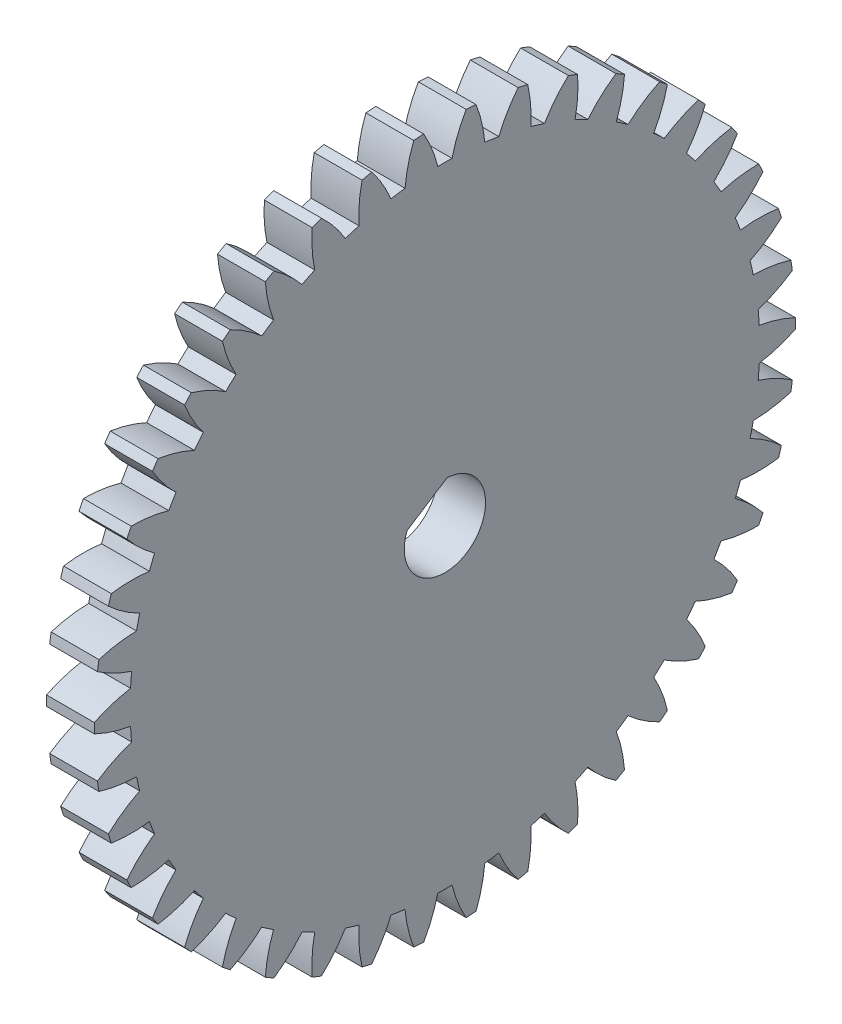
SolidWorks part; units mm, degrees
ref_plane "Plane1" through (0, 0, 0) normal (0, 0, 1) x (1, 0, 0)
ref_plane "Plane2" through (0, 0, 0) normal (0, 1, 0) x (1, 0, 0)
ref_plane "Plane3" through (0, 0, 0) normal (1, 0, 0) x (0, 0, -1)
sketch "HoldingSke" plane through (0, 0, 0) normal (0, 1, 0) x (1, 0, 0)
  line L0 (0, 0) -> (0.7431, -0.6691)
  line L1 (-15, 0) -> (100, 0) construction
  line L2 (0, 0) -> (-2.1039, 2.3779)
  line L3 (0, 0) -> (-11.863, 4.5341)
  line L4 (0, 0) -> (6.4178, 5.7786)
  line L5 (0, 0) -> (-46.8476, -17.4728)
  line L6 (0, 0) -> (-2.4869, -1.6779)
  line L7 (-2.1039, 2.3779) -> (8.6586, 51.2059)
  line L8 (-76.2, 54.61) -> (-76.1, 54.61)
  line L9 (-71.009, 38.7566) -> (-53.1078, 45.2721)
  line L10 (-76.2, 71.12) -> (104.1128, 71.12)
  line L11 (0, 0) -> (-3, 0)
  line L12 (-76.2, 101.6) -> (-76.162, 101.6)
  line L13 (24.9733, 27.94) -> (52.9518, 28.4284)
  line L14 (24.9733, 27.94) -> (24.9743, 27.94)
  line L15 (24.9733, 27.94) -> (100.4006, 29.5858)
  line L16 (-63.627, -1) -> (-12.827, -1)
  circle A0 centre (0, 0) radius 0.5
  circle A1 centre (0, 0) radius 19.749
  circle A2 centre (0, 0) radius 37.5
  circle A3 centre (0, 0) radius 0.5
  dimension "MHD" = 39.498
  dimension "Hub_dia" = 75
  dimension "Bore" = 1
  dimension "MBD" = 1
  dimension "Num_teeth" = 42
  dimension "Pitch" = 1
  dimension "Overall_len" = 50
  dimension "Show_teeth" = 42
  dimension "Thickness" = 3
  dimension "OAL" = 50.0001
  dimension "T_dim" = 0.1
  dimension "Ap" = 20
  dimension "H" = 19.05
  dimension "Pitch_radius" = 180.3128
  dimension "Width" = 3
  dimension "Backlash" = 0.038
  dimension "Addendum_fac" = 1
  dimension "Dedendum_fac" = 1.25
  dimension "Clearance_fac" = 0.25
  dimension "Dedendum_add" = 0.001
  dimension "Module" = 1
sketch "BasProSke" plane through (0, 0, 0) normal (0, 1, 0) x (1, 0, 0)
  line L0 (-10, 0) -> (60, 0) construction
  line L1 (0, 0) -> (0, 22)
  line L2 (0, 0) -> (3, 0)
  line L3 (3, 0) -> (3, 22)
  line L4 (3, 22) -> (0, 22)
  dimension "Thickness" = 3
  dimension "Diameter" = 44
revolve "Base-Revolve" add sketch "BasProSke" angle 360 about L0
sketch "TooCutSke" plane through (0, 0, 0) normal (1, 0, 0) x (0, 0, -1)
  line L1 (0, 0) -> (0, 107) construction
  line L2 (0, 0) -> (-0.8517, 20.9827) construction
  line L3 (0, 0) -> (-3.1368, 41.858) construction
  line L4 (-0.8517, 20.9827) -> (-1.5684, 20.929) construction
  arc A0 (0.4461, 19.744) -> (-0.4461, 19.744) centre (0, 0) ccw
  arc A1 (1.3487, 21.9841) -> (-1.3487, 21.9841) centre (0, 0) ccw
  circle A2 centre (0, 0) radius 21 construction
  circle A3 centre (0, 0) radius 19.7335 construction
  arc A4 (-0.4461, 19.744) -> (-1.3487, 21.9841) centre (-8.6078, 17.7572) ccw
  arc A5 (1.3487, 21.9841) -> (0.4461, 19.744) centre (8.6078, 17.7572) ccw
  dimension "Root_dia" = 39.498
  dimension "Overcut_dia" = 44.0508
  dimension "Pitch_dia" = 42
  dimension "Base_dia" = 39.4671
  dimension "Flank_rad" = 8.4
  dimension "Half_ang" = 4.286
  dimension "Half_CT" = 0.7187
extrude "ToothCut" cut sketch "TooCutSke" along normal through all
fillet "Breaks" [suppressed] radius 0.02
fillet "RootFillets" [suppressed] radius 0.251
pattern_circular "TeethCuts" count 42 every 8.571 about axis through (-10, 0, 0) along (1, 0, 0) of "ToothCut", "RootFillets", "Breaks"
sketch "HubNeaOneSke" plane through (0, 0, 0) normal (-1, 0, 0) x (0, 0, 1)
  circle A0 centre (0, 0) radius 19.749
  dimension "Diameter" = 39.498
extrude "HubNearOne" [suppressed] add sketch "HubNeaOneSke" along normal blind 47.0001
sketch "HubNeaBotSke" plane through (0, 0, 0) normal (-1, 0, 0) x (0, 0, 1)
  circle A0 centre (0, 0) radius 19.749
  dimension "Diameter" = 39.498
extrude "HubNearBoth" [suppressed] add sketch "HubNeaBotSke" along normal blind 23.5
ref_plane "FarPln" through (3, 0, 0) normal (1, 0, 0) x (0, 0, -1)
sketch "HubFarSke" plane through (3, 0, 0) normal (1, 0, 0) x (0, 0, -1)
  circle A0 centre (0, 0) radius 19.749
  dimension "Diameter" = 39.498
extrude "HubFar" [suppressed] add sketch "HubFarSke" along normal blind 23.5
sketch "BorSke" plane through (0, 0, 0) normal (1, 0, 0) x (0, 0, -1)
  line L0 (-2.38, 0.9154) -> (0.138, 2.5463)
  arc A0 (-2.38, 0.9154) -> (0.138, 2.5463) centre (0, 0) ccw
  dimension "D1" = 3
  dimension "D2" = 2.55
extrude "Bore" cut sketch "BorSke" along normal mid plane 100.0001
sketch "KeySke" plane through (0, 0, 0) normal (1, 0, 0) x (0, 0, -1)
  line L0 (-0.05, 0) -> (-0.05, 0.6)
  line L1 (-0.05, 0.6) -> (0.05, 0.6)
  line L2 (0.05, 0.6) -> (0.05, 0)
  line L3 (0, 0) -> (0, 34) construction
  line L4 (-0.05, 0) -> (0.05, 0)
  dimension "Offset" = 0.6
  dimension "Width" = 0.1
extrude "Keyway" [suppressed] cut sketch "KeySke" along normal mid plane 100.0001
pattern_circular "Keyway2" [suppressed] count 2 every 90 about axis through (-10, 0, 0) along (1, 0, 0)
equation "' \"Module@HoldingSke\" = 6.35"
equation "' \"Num_teeth@HoldingSke\" = 12"
equation "' \"Ap@HoldingSke\" =  20"
equation "' \"Ap@HoldingSke\" = 20"
equation "' \"Width@HoldingSke\" = 0.5 * 25.4"
equation "' \"Hub_dia@HoldingSke\"= 1 * 25.4"
equation "' \"Hub_dia@HoldingSke\" = 1 * 25.4"
equation "' \"Overall_len@HoldingSke\" = 1.0 * 25.4"
equation "' \"Bore@HoldingSke\" = 0.75 * 25.4"
equation "' \"T_dim@HoldingSke\" = 0.1 * 25.4"
equation "' \"Width@KeySke\" = 0.25 * 25.4"
equation "' \"Show_teeth@HoldingSke\" = 13"
equation "' \"Backlash@HoldingSke\" = 0.009 * 25.4"
equation "' \"Addendum_fac@HoldingSke\" = 1.0"
equation "' \"Dedendum_fac@HoldingSke\" = 1.25"
equation "' \"Dedendum_add@HoldingSke\" = 0.00005 * 25.4"
equation "' \"Clearance_fac@HoldingSke\" = 0.25"
equation "\"Pitch@HoldingSke\" = 1 / \"Module@HoldingSke\""
equation "\"Overcut_dia@TooCutSke\" = (\"Num_teeth@HoldingSke\" + 2 * \"Addendum_fac@HoldingSke\") / \"Pitch@HoldingSke\" + 0.002 * 25.4"
equation "\"Pitch_dia@TooCutSke\" = \"Num_teeth@HoldingSke\" / \"Pitch@HoldingSke\""
equation "\"Base_dia@TooCutSke\" = \"Num_teeth@HoldingSke\" / \"Pitch@HoldingSke\" * cos((\"Ap@HoldingSke\"  * 3.14159265 / 180))"
equation "\"Root_dia@TooCutSke\" = (\"Num_teeth@HoldingSke\" + 2) / \"Pitch@HoldingSke\" - 2 * (\"Addendum_fac@HoldingSke\" + \"Dedendum_fac@HoldingSke\") / \"Pitch@HoldingSke\" - \"Dedendum_add@HoldingSke\" * 2"
equation "\"Half_ang@TooCutSke\" = 180 / \"Num_teeth@HoldingSke\""
equation "\"Half_CT@TooCutSke\" = \"Num_teeth@HoldingSke\" / \"Pitch@HoldingSke\" * sin((3.14159265 / 2 / \"Num_teeth@HoldingSke\")) / 2 - 7 * \"Backlash@HoldingSke\" / 4"
equation "\"Flank_rad@TooCutSke\" = \"Num_teeth@HoldingSke\" / \"Pitch@HoldingSke\" / 5"
equation "\"Radius@RootFillets\" = \"Clearance_fac@HoldingSke\" / \"Pitch@HoldingSke\" + \"Dedendum_add@HoldingSke\""
equation "\"Break_rad@Breaks\" = 0.02 / \"Pitch@HoldingSke\""
equation "\"Thickness@HoldingSke\" = \"Width@HoldingSke\""
equation "\"OAL@HoldingSke\" = \"Thickness@HoldingSke\""
equation "\"MHD@HoldingSke\" = (\"Num_teeth@HoldingSke\" + 2) / \"Pitch@HoldingSke\" - 2 * (\"Addendum_fac@HoldingSke\" + \"Dedendum_fac@HoldingSke\")  / \"Pitch@HoldingSke\" - \"Dedendum_add@HoldingSke\" * 2"
equation "\"MBD@HoldingSke\" = (\"Num_teeth@HoldingSke\" + 2) / \"Pitch@HoldingSke\" - 2 * (\"Addendum_fac@HoldingSke\" + \"Dedendum_fac@HoldingSke\")  / \"Pitch@HoldingSke\" - \"Dedendum_add@HoldingSke\" * 2 - 0.002 * 25.4"
equation "\"MHD@HoldingSke\" = ((sgn( \"MHD@HoldingSke\" - \"Hub_dia@HoldingSke\" )-1)*( \"MHD@HoldingSke\" - \"Hub_dia@HoldingSke\" ))/-2+ \"Hub_dia@HoldingSke\""
equation "\"MBD@HoldingSke\" = ((sgn( \"MBD@HoldingSke\" - \"Bore@HoldingSke\" )-1)*( \"MBD@HoldingSke\" - \"Bore@HoldingSke\" ))/-2+ \"Bore@HoldingSke\""
equation "\"OAL@HoldingSke\" = ((sgn( \"OAL@HoldingSke\" - \"Overall_len@HoldingSke\" )+1)*( \"OAL@HoldingSke\" - \"Overall_len@HoldingSke\" ))/2 + \"Overall_len@HoldingSke\" + 0.000002 * 25.4"
equation "\"Num_teeth@TeethCuts\" = int( \"Show_teeth@HoldingSke\" ) + 1"
equation "\"Num_teeth@TeethCuts\" = ((sgn( \"Num_teeth@TeethCuts\" - \"Num_teeth@HoldingSke\" )-1)*( \"Num_teeth@TeethCuts\" - \"Num_teeth@HoldingSke\" ))/-2+ \"Num_teeth@HoldingSke\""
equation "\"Num_teeth@TeethCuts\" = ((sgn( \"Num_teeth@TeethCuts\" - 2.0)+1)*( \"Num_teeth@TeethCuts\" - 2.0))/2 +2.0"
equation "\"Angle@TeethCuts\" = 360.0 / \"Num_teeth@HoldingSke\""
equation "\"Diameter@BasProSke\" = (\"Num_teeth@HoldingSke\" + 2 * \"Addendum_fac@HoldingSke\") / \"Pitch@HoldingSke\""
equation "\"Thickness@BasProSke\"  = \"Thickness@HoldingSke\""
equation "' \"Fillet_rad@BasProSke\" =  \"Thickness@HoldingSke\" * 0.05"
equation "' \"Fillet_rad@BasProSke\" = \"Thickness@HoldingSke\" * 0.05"
equation "\"MHD@HoldingSke\" = ((sgn( \"MHD@HoldingSke\" - \"Root_dia@TooCutSke\" )-1)*( \"MHD@HoldingSke\" - \"Root_dia@TooCutSke\" ))/-2+ \"Root_dia@TooCutSke\""
equation "\"Diameter@HubNeaOneSke\" = \"MHD@HoldingSke\""
equation "\"Length@HubNearOne\" = \"OAL@HoldingSke\" - \"Thickness@BasProSke\""
equation "\"Diameter@HubNeaBotSke\" = \"MHD@HoldingSke\""
equation "\"Length@HubNearBoth\" = ( \"OAL@HoldingSke\" - \"Thickness@BasProSke\" ) / 2.0"
equation "\"Thickness@FarPln\" = \"Thickness@BasProSke\""
equation "\"Diameter@HubFarSke\" = \"MHD@HoldingSke\""
equation "\"Length@HubFar\" = ( \"OAL@HoldingSke\" - \"Thickness@BasProSke\" ) / 2.0"
equation "\"D1@Bore\" = \"OAL@HoldingSke\" * 2.0"
equation "\"D1@Keyway\" = \"OAL@HoldingSke\" * 2.0"
equation "\"Offset@KeySke\" = \"T_dim@HoldingSke\" + \"MBD@HoldingSke\" / 2.0"
